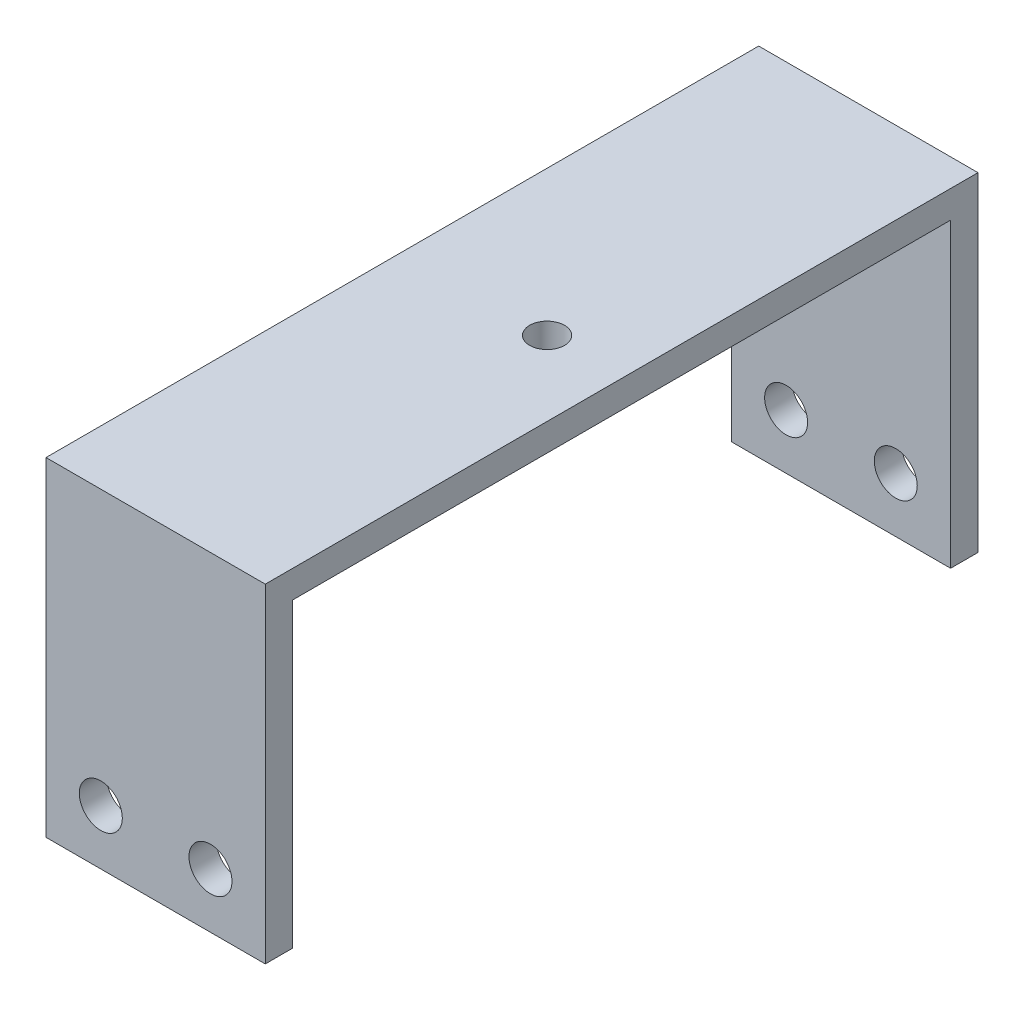
SolidWorks part; units mm, degrees
ref_plane "Front Plane" through (0, 0, 0) normal (0, 0, 1) x (1, 0, 0)
ref_plane "Top Plane" through (0, 0, 0) normal (0, 1, 0) x (1, 0, 0)
ref_plane "Right Plane" through (0, 0, 0) normal (1, 0, 0) x (0, 0, -1)
sketch "Sketch1" plane through (0, 0, 0) normal (1, 0, 0) x (0, 0, -1)
  line L0 (82.55, 0) -> (79.375, 0)
  line L1 (0, 0) -> (3.175, 0)
  line L2 (0, 0) -> (0, 38.1)
  line L3 (0, 38.1) -> (82.55, 38.1)
  line L4 (82.55, 0) -> (82.55, 38.1)
  line L5 (3.175, 0) -> (3.175, 34.925)
  line L6 (3.175, 34.925) -> (79.375, 34.925)
  line L7 (79.375, 34.925) -> (79.375, 0)
  dimension "D1" = 82.55
  dimension "D2" = 38.1
  dimension "D3" = 3.175
  dimension "D4" = 3.175
extrude "Boss-Extrude1" add sketch "Sketch1" along normal blind 25.4
hole_wizard "#10-32 Tapped Hole1" positions "Sketch3" profile "Sketch2" tap size "#10-32" standard "ANSI Inch"
sketch "Sketch3" plane through (0, 38.1, 0) normal (0, 1, 0) x (1, 0, 0)
  line L0 (25.4, 82.55) -> (25.4, 0) construction
  line L2 (25.4, 41.275) -> (9.8705, 41.275) construction
  point P0 (16.764, 41.275)
  dimension "D1" = 8.636
sketch "Sketch2" plane through (16.764, 38.1, -41.275) normal (1, 0, 0) x (0, 0, 1)
  line L0 (0, 0) -> (0, 14.9293)
  line L1 (0, 14.9293) -> (2.0193, 13.716)
  line L2 (2.0193, 13.716) -> (2.0193, 0)
  line L5 (2.0193, 0) -> (0, 0)
  line L10 (0, 14.9293) -> (-2.0193, 13.716) construction
  line L11 (0, -6.35) -> (0, 107.95) construction
  dimension "Tap Drill Dia." = 4.0386
  dimension "Tap Drill Depth" = 13.716
  dimension "Drill Angle" = 118
cosmetic thread "Hole Thread1"
hole_wizard "#9 (0.196) Diameter Hole1" positions "Sketch6" profile "Sketch5" hole size "#9" standard "ANSI Inch" end condition through all
sketch "Sketch6" plane through (0, 0, 0) normal (0, 0, 1) x (1, 0, 0)
  line L0 (25.4, 38.1) -> (25.4, 0) construction
  line L1 (25.4, 0) -> (0, 0) construction
  point P0 (6.35, 6.35)
  point P2 (19.05, 6.35)
  dimension "D1" = 12.7
  dimension "D2" = 6.35
  dimension "D3" = 6.35
sketch "Sketch5" plane through (6.35, 6.35, 0) normal (1, 0, 0) x (0, -1, 0)
  line L0 (0, 0) -> (0, 82.55)
  line L1 (0, 82.55) -> (2.4892, 82.55)
  line L2 (2.4892, 82.55) -> (2.4892, 0)
  line L5 (2.4892, 0) -> (0, 0)
  line L11 (0, -6.35) -> (0, 107.95) construction
  dimension "Thru Hole Dia." = 4.9784
  dimension "Thru Hole Depth" = 82.55
